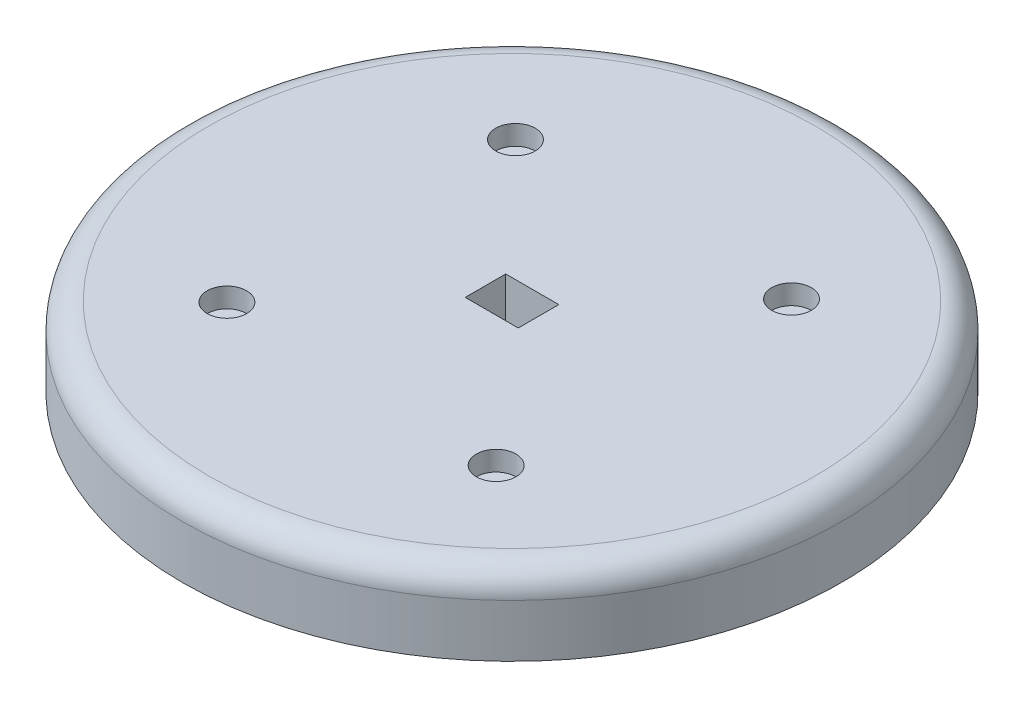
SolidWorks part; units mm, degrees
ref_plane "前视基准面" through (0, 0, 0) normal (0, 0, 1) x (1, 0, 0)
ref_plane "上视基准面" through (0, 0, 0) normal (0, 1, 0) x (1, 0, 0)
ref_plane "右视基准面" through (0, 0, 0) normal (1, 0, 0) x (0, 0, -1)
sketch "草图1" plane through (0, 0, 0) normal (0, 1, 0) x (1, 0, 0)
  circle A0 centre (0, 0) radius 50
extrude "凸台-拉伸1" add sketch "草图1" along normal blind 12 contours A0
fillet "圆角1" radius 4 1 edges at (0, 12, 50)
sketch "草图5" plane through (0, 12, 0) normal (0, 1, 0) x (1, 0, 0)
  line L0 (0, 31.9298) -> (0, -28.8611) construction
  line L1 (-34.0204, 0) -> (36.7831, -0.8667) construction
  circle A0 centre (-20.9418, 21.467) radius 3
  circle A1 centre (20.9418, 21.467) radius 3
  circle A2 centre (20.3998, -22.8059) radius 3
  circle A3 centre (-21.4711, -21.7807) radius 3
  dimension "D1" = 6
extrude "切除-拉伸1" cut sketch "草图5" against normal blind 3
sketch "草图7" plane through (0, 12, 0) normal (0, 1, 0) x (1, 0, 0)
  line L1 (4.025, -3.075) -> (-4.025, -3.075)
  line L2 (4.025, -3.075) -> (4.025, 3.075)
  line L3 (4.025, 3.075) -> (-4.025, 3.075)
  line L4 (-4.025, -3.075) -> (-4.025, 3.075)
  line L5 (4.025, -3.075) -> (-4.025, 3.075) construction
  line L6 (4.025, 3.075) -> (-4.025, -3.075) construction
  point P0 (0, 0)
  dimension "D1" = 8.05
  dimension "D2" = 6.15
extrude "切除-拉伸2" cut sketch "草图7" against normal through all
sketch "草图8" plane through (0, 12, 0) normal (0, 1, 0) x (1, 0, 0)
  line L1 (-20.9418, -21.467) -> (20.9418, -21.467)
  line L2 (-20.9418, -21.467) -> (-20.9418, 21.467)
  line L3 (-20.9418, 21.467) -> (20.9418, 21.467)
  line L4 (20.9418, -21.467) -> (20.9418, 21.467)
  line L5 (-20.9418, -21.467) -> (20.9418, 21.467) construction
  line L6 (-20.9418, 21.467) -> (20.9418, -21.467) construction
  line L7 (0, 0) -> (0, 21.467)
  point P0 (0, 0)
  dimension "D1" = 20.9418
  dimension "D2" = 21.467
